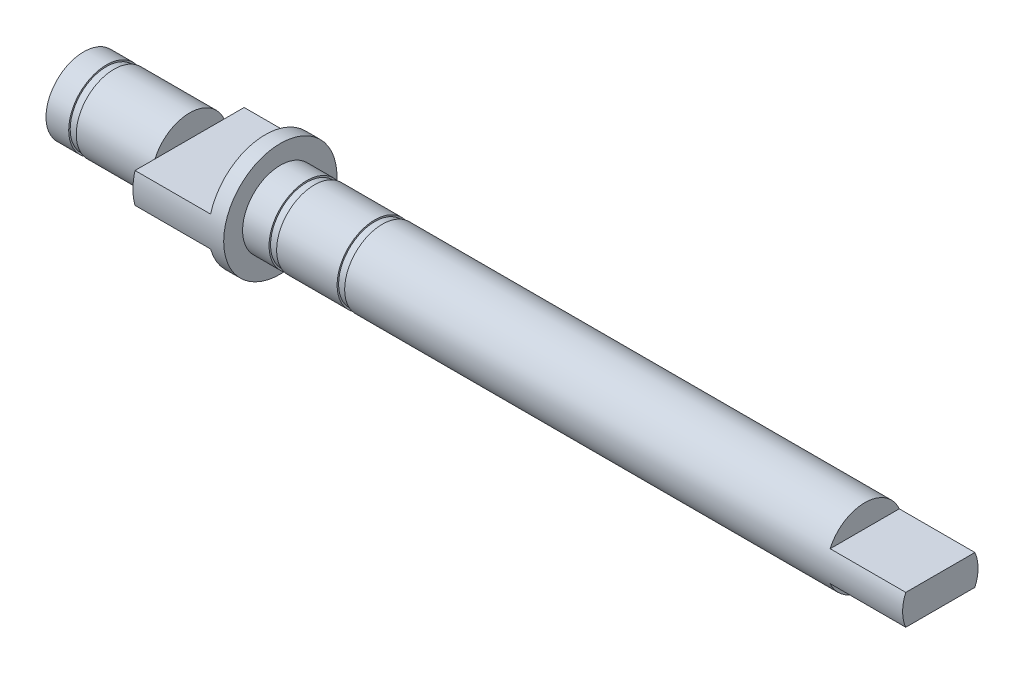
SolidWorks part; units mm, degrees
material "ASTM A36 Steel"
ref_plane "Front Plane" through (0, 0, 0) normal (0, 0, 1) x (1, 0, 0)
ref_plane "Top Plane" through (0, 0, 0) normal (0, 1, 0) x (1, 0, 0)
ref_plane "Right Plane" through (0, 0, 0) normal (1, 0, 0) x (0, 0, -1)
sketch "Sketch3" plane through (0, 0, 0) normal (0, 1, 0) x (1, 0, 0)
  line L0 (0, 0) -> (41.8214, 0) construction
  line L1 (0, 0) -> (113.3, 0)
  line L2 (113.3, 0) -> (113.3, 4.99)
  line L3 (113.3, 4.99) -> (39.5, 4.99)
  line L4 (39.5, 4.99) -> (39.5, 4.79)
  line L5 (39.5, 4.79) -> (38.5, 4.79)
  line L6 (38.5, 4.79) -> (38.5, 4.99)
  line L7 (38.5, 4.99) -> (30.5, 4.99)
  line L8 (30.5, 4.99) -> (30.5, 4.79)
  line L9 (30.5, 4.79) -> (29.5, 4.79)
  line L10 (29.5, 4.79) -> (29.5, 4.99)
  line L11 (29.5, 4.99) -> (26, 4.99)
  line L12 (26, 4.99) -> (26, 7.49)
  line L13 (26, 7.49) -> (14, 7.49)
  line L14 (14, 7.49) -> (14, 4.99)
  line L15 (14, 4.99) -> (4, 4.99)
  line L16 (4, 4.99) -> (4, 4.79)
  line L17 (4, 4.79) -> (3, 4.79)
  line L18 (3, 4.79) -> (3, 4.99)
  line L19 (3, 4.99) -> (0, 4.99)
  line L20 (0, 4.99) -> (0, 0)
  dimension "D1" = 4.99
  dimension "D2" = 0.2
  dimension "D3" = 1
  dimension "D4" = 3
  dimension "D5" = 10
  dimension "D6" = 12
  dimension "D7" = 3.5
  dimension "D8" = 8
  dimension "D9" = 87.3
  dimension "D10" = 2.5
revolve "Revolve1" add sketch "Sketch3" angle 360 about L0
sketch "Sketch10" plane through (14, 0, 0) normal (-1, 0, 0) x (0, 0, 1)
  line L0 (7.2284, 2) -> (-7.2284, 2)
  line L2 (7.2284, -2) -> (-7.2284, -2)
  arc A1 (-7.2284, 2) -> (7.2284, 2) centre (0, 0) cw
  arc A2 (-7.2284, -2) -> (7.2284, -2) centre (0, 0) ccw
  point P2 (0, 7.5)
  point P4 (0, -7.5)
  dimension "D1" = 4
  dimension "D3" = 7.5
  dimension "D4" = 7.5
extrude "Cut-Extrude8" cut sketch "Sketch10" against normal blind 10
sketch "Sketch11" plane through (113.3, 0, 0) normal (1, 0, 0) x (0, 0, -1)
  line L5 (-4.5826, -2) -> (4.5826, -2)
  line L7 (4.5826, 2) -> (-4.5826, 2)
  arc A2 (-4.5826, -2) -> (4.5826, -2) centre (0, 0) ccw
  arc A3 (4.5826, 2) -> (-4.5826, 2) centre (0, 0) ccw
  point P5 (0, 2)
  dimension "D1" = 10
  dimension "D2" = 4
extrude "Cut-Extrude9" cut sketch "Sketch11" against normal blind 10
